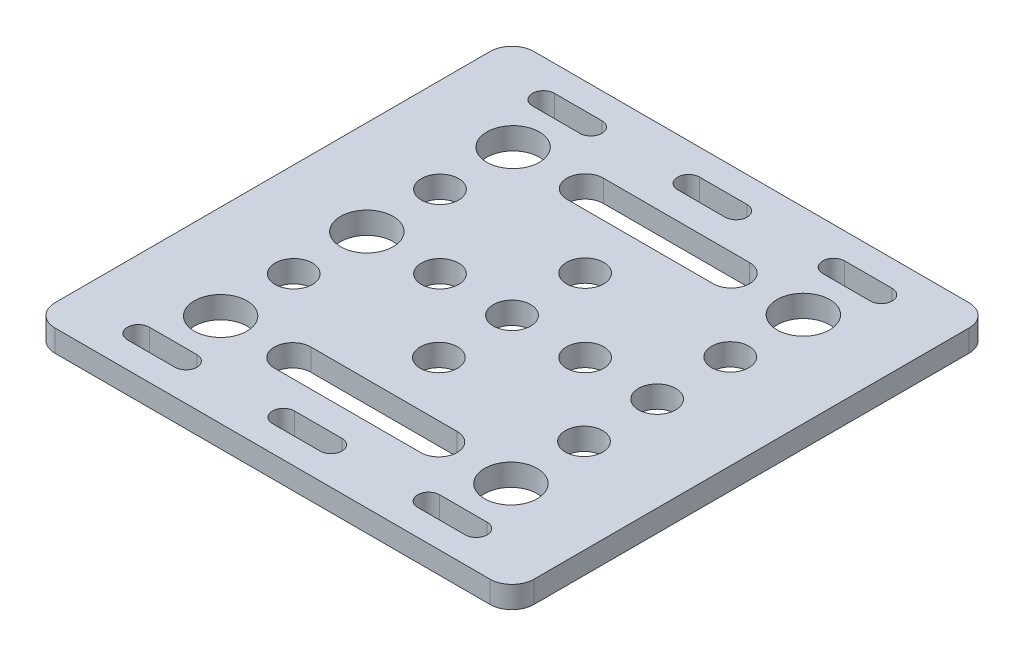
SolidWorks part; units mm, degrees
ref_plane "Płaszczyzna przednia" through (0, 0, 0) normal (0, 0, 1) x (1, 0, 0)
ref_plane "Płaszczyzna górna" through (0, 0, 0) normal (0, 1, 0) x (1, 0, 0)
ref_plane "Płaszczyzna prawa" through (0, 0, 0) normal (1, 0, 0) x (0, 0, -1)
sketch "Szkic1" plane through (0, 0, 0) normal (0, 1, 0) x (1, 0, 0)
  line L0 (9.35, 60.45) -> (15.85, 60.45) construction
  line L1 (3, 0) -> (62.5, 0)
  line L2 (0, 3) -> (0, 62.5)
  line L3 (3, 65.5) -> (62.5, 65.5)
  line L4 (65.5, 3) -> (65.5, 62.5)
  line L5 (9.35, 61.95) -> (15.85, 61.95)
  line L6 (9.35, 58.95) -> (15.85, 58.95)
  line L7 (29.2, 58.95) -> (35.7, 58.95)
  line L8 (29.2, 61.95) -> (35.7, 61.95)
  line L9 (29.2, 60.45) -> (35.7, 60.45) construction
  line L10 (49.05, 58.95) -> (55.55, 58.95)
  line L11 (49.05, 61.95) -> (55.55, 61.95)
  line L12 (49.05, 60.45) -> (55.55, 60.45) construction
  line L13 (29.2, 3.55) -> (35.7, 3.55)
  line L14 (29.2, 6.55) -> (35.7, 6.55)
  line L15 (29.2, 5.05) -> (35.7, 5.05) construction
  line L16 (49.05, 3.55) -> (55.55, 3.55)
  line L17 (49.05, 6.55) -> (55.55, 6.55)
  line L18 (49.05, 5.05) -> (55.55, 5.05) construction
  line L19 (9.35, 3.55) -> (15.85, 3.55)
  line L20 (9.35, 6.55) -> (15.85, 6.55)
  line L21 (9.35, 5.05) -> (15.85, 5.05) construction
  line L22 (22.75, 12.75) -> (42.75, 12.75) construction
  line L23 (22.75, 15.25) -> (42.75, 15.25)
  line L24 (22.75, 10.25) -> (42.75, 10.25)
  line L25 (22.75, 50.25) -> (42.75, 50.25)
  line L26 (22.75, 55.25) -> (42.75, 55.25)
  line L27 (22.75, 52.75) -> (42.75, 52.75) construction
  arc A0 (9.35, 61.95) -> (9.35, 58.95) centre (9.35, 60.45) ccw
  arc A1 (15.85, 58.95) -> (15.85, 61.95) centre (15.85, 60.45) ccw
  arc A2 (29.2, 61.95) -> (29.2, 58.95) centre (29.2, 60.45) ccw
  arc A3 (35.7, 58.95) -> (35.7, 61.95) centre (35.7, 60.45) ccw
  arc A4 (49.05, 61.95) -> (49.05, 58.95) centre (49.05, 60.45) ccw
  arc A5 (55.55, 58.95) -> (55.55, 61.95) centre (55.55, 60.45) ccw
  arc A6 (29.2, 6.55) -> (29.2, 3.55) centre (29.2, 5.05) ccw
  arc A7 (35.7, 3.55) -> (35.7, 6.55) centre (35.7, 5.05) ccw
  arc A8 (49.05, 6.55) -> (49.05, 3.55) centre (49.05, 5.05) ccw
  arc A9 (55.55, 3.55) -> (55.55, 6.55) centre (55.55, 5.05) ccw
  arc A10 (9.35, 6.55) -> (9.35, 3.55) centre (9.35, 5.05) ccw
  arc A11 (15.85, 3.55) -> (15.85, 6.55) centre (15.85, 5.05) ccw
  circle A12 centre (12.9, 52.75) radius 3.6
  circle A13 centre (52.6, 52.75) radius 3.6
  circle A15 centre (52.6, 12.75) radius 3.6
  circle A16 centre (12.9, 32.75) radius 3.6
  circle A17 centre (12.9, 12.75) radius 3.6
  circle A18 centre (52.6, 32.75) radius 3.6 [skipped]
  circle A19 centre (12.9, 42.75) radius 2.55
  circle A20 centre (32.75, 42.75) radius 2.55
  circle A21 centre (52.6, 42.75) radius 2.55
  circle A22 centre (32.75, 32.75) radius 2.55
  circle A23 centre (52.6, 32.75) radius 2.55
  circle A24 centre (32.75, 22.75) radius 2.55
  circle A25 centre (52.6, 22.75) radius 2.55
  circle A27 centre (12.9, 22.75) radius 2.55
  circle A28 centre (12.9, 32.75) radius 2.55 [skipped]
  circle A29 centre (42.75, 32.75) radius 2.55
  circle A30 centre (42.75, 32.75) radius 2.55
  circle A31 centre (22.9, 32.75) radius 2.55
  arc A32 (0, 62.5) -> (3, 65.5) centre (3, 62.5) cw
  arc A33 (62.5, 65.5) -> (65.5, 62.5) centre (62.5, 62.5) cw
  arc A34 (62.5, 0) -> (65.5, 3) centre (62.5, 3) ccw
  arc A35 (3, 0) -> (0, 3) centre (3, 3) cw
  arc A36 (22.75, 15.25) -> (22.75, 10.25) centre (22.75, 12.75) ccw
  arc A37 (42.75, 10.25) -> (42.75, 15.25) centre (42.75, 12.75) ccw
  arc A38 (22.75, 55.25) -> (22.75, 50.25) centre (22.75, 52.75) ccw
  arc A39 (42.75, 50.25) -> (42.75, 55.25) centre (42.75, 52.75) ccw
  point P7 (12.6, 60.45)
  point P17 (32.45, 60.45)
  point P24 (52.3, 60.45)
  point P31 (32.45, 5.05)
  point P38 (52.3, 5.05)
  point P45 (12.6, 5.05)
  point P87 (65.5, 65.5)
  point P90 (65.5, 0)
  point P93 (0, 0)
  point P96 (32.75, 12.75)
  point P104 (32.75, 52.75)
  dimension "D9" = 7.2
  dimension "D10" = 12.75
  dimension "D11" = 12.9
  dimension "D14" = 5.1
  dimension "D15" = 12.9
  dimension "D16" = 22.75
  dimension "D21" = 3
  dimension "D1" = 65.5
  dimension "D2" = 65.5
  dimension "D3" = 9.35
  dimension "D4" = 6.5
  dimension "D5" = 5.05
  dimension "D6" = 3
  dimension "D22" = 5
  dimension "D23" = 32.75
  dimension "D24" = 20
  dimension "D25" = 52.75
  dimension "D7" = 3
  dimension "D8" = 2
  dimension "D12" = 2
  dimension "D13" = 3
  dimension "D17" = 3
  dimension "D18" = 3
  dimension "D19" = 2
  dimension "D20" = 2
  dimension "D26" = 2
extrude "Dodanie-wyciągnięcie1" add sketch "Szkic1" along normal blind 3 contours A35 L1 A34 L4 A33 L3 A32 L2 A39 L25 A38 L26 A37 L24 A36 L23 A31 A29 A27 A25 A24 A23 A22 A21 A20 A19 A17 A16 A15 A13 A12 A11 L19
